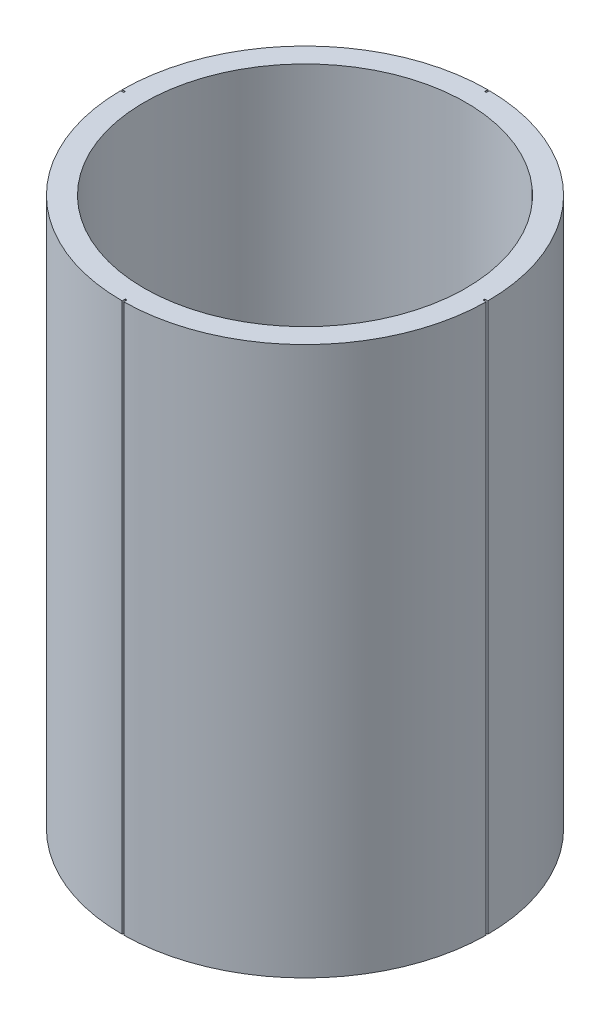
SolidWorks part; units mm, degrees
ref_plane "Front Plane" through (0, 0, 0) normal (0, 0, 1) x (1, 0, 0)
ref_plane "Top Plane" through (0, 0, 0) normal (0, 1, 0) x (1, 0, 0)
ref_plane "Right Plane" through (0, 0, 0) normal (1, 0, 0) x (0, 0, -1)
sketch "Sketch1" plane through (0, 0, 0) normal (0, 1, 0) x (1, 0, 0)
  line L0 (0, 5) -> (0, 4.9123)
  line L1 (-5, 0) -> (-4.9151, 0)
  line L2 (-4.9998, -0.0436) -> (-4.9151, -0.0429)
  line L3 (-4.9151, 0) -> (-4.9151, -0.0429)
  line L4 (0.0436, 4.9998) -> (0.0429, 4.9123)
  line L5 (0, 4.9123) -> (0.0429, 4.9123)
  line L7 (4.9151, 0) -> (5, 0)
  line L8 (0.0436, -4.9998) -> (0.0429, -4.9123)
  line L9 (0, -4.9123) -> (0.0429, -4.9123)
  line L10 (0, -5) -> (0, -4.9123)
  line L11 (4.9998, -0.0436) -> (4.9151, -0.0429)
  line L12 (4.9151, 0) -> (4.9151, -0.0429)
  arc A0 (0, 5) -> (-5, 0) centre (0, 0) ccw
  circle A1 centre (0, 0) radius 4.4
  arc A2 (-4.9998, -0.0436) -> (0, -5) centre (0, 0) ccw
  arc A3 (5, 0) -> (0.0436, 4.9998) centre (0, 0) ccw
  arc A4 (0.0436, -4.9998) -> (4.9998, -0.0436) centre (0, 0) ccw
  dimension "D1" = 8.8
  dimension "D2" = 10
  dimension "D3" = 0.5
  dimension "D4" = 0.5
extrude "Boss-Extrude1" add sketch "Sketch1" along normal blind 15
